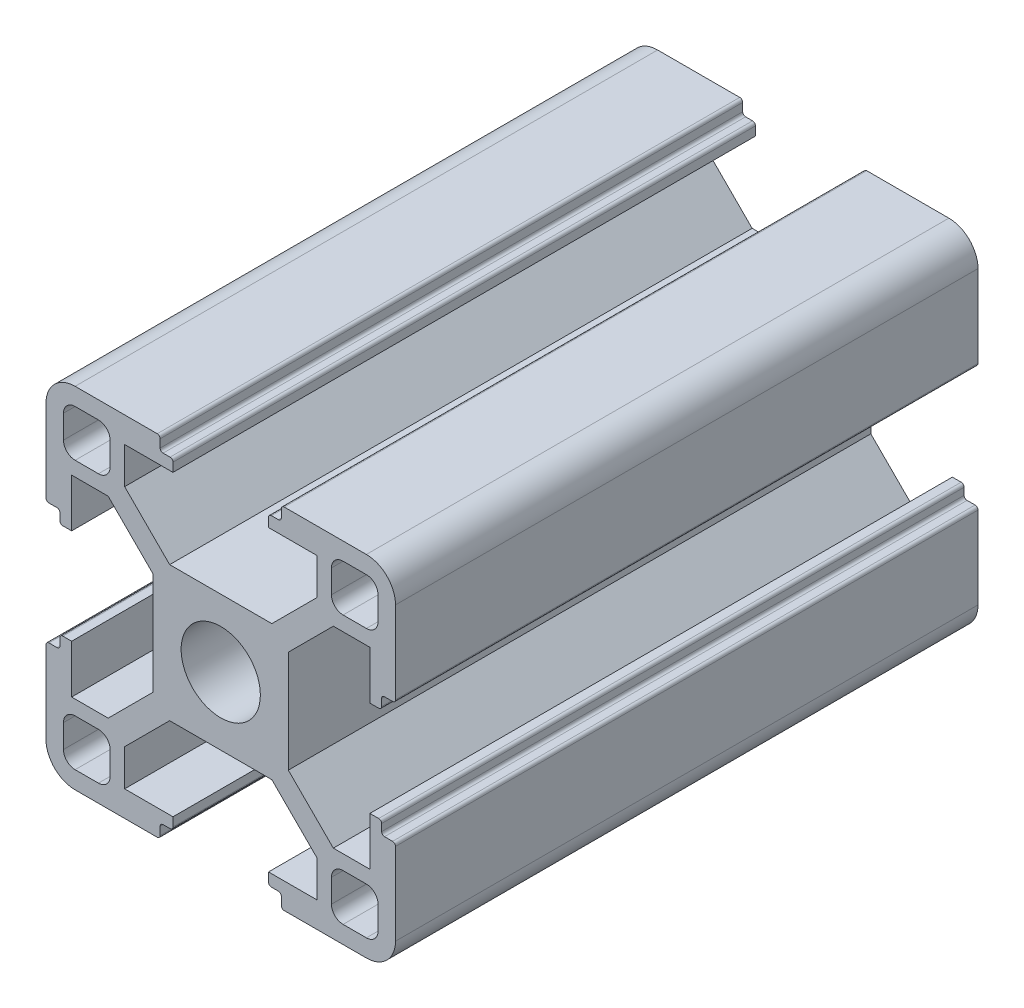
SolidWorks part; units mm, degrees
ref_plane "Front Plane" through (0, 0, 0) normal (0, 0, 1) x (1, 0, 0)
ref_plane "Top Plane" through (0, 0, 0) normal (0, 1, 0) x (1, 0, 0)
ref_plane "Right Plane" through (0, 0, 0) normal (1, 0, 0) x (0, 0, -1)
sketch "Sketch1" plane through (0, 0, 0) normal (0, 0, 1) x (1, 0, 0)
  line L0 (0, -5.8) -> (0, 5.8) construction
  line L1 (0, 0) -> (-15, 15) construction
  line L2 (-15, 15) -> (-5.2, 15)
  line L3 (-5.2, 15) -> (-5.2, 13.8083)
  line L4 (-5.2, 13.8083) -> (-4.1, 13.8083)
  line L5 (-4.1, 13.8083) -> (-4.1, 12.8)
  line L6 (-4.1, 12.8) -> (-8.25, 12.8)
  line L7 (-8.25, 12.8) -> (-8.25, 9.6642)
  line L8 (-8.25, 9.6642) -> (-4.3858, 5.8)
  line L9 (-4.3858, 5.8) -> (4.3858, 5.8)
  line L10 (-5.8, 4.3858) -> (-5.8, -4.3858)
  line L11 (-9.6642, 8.25) -> (-5.8, 4.3858)
  line L12 (-12.8, 8.25) -> (-9.6642, 8.25)
  line L13 (-12.8, 4.1) -> (-12.8, 8.25)
  line L14 (-13.8083, 4.1) -> (-12.8, 4.1)
  line L15 (-13.8083, 5.2) -> (-13.8083, 4.1)
  line L16 (-15, 5.2) -> (-13.8083, 5.2)
  line L17 (-15, 15) -> (-15, 5.2)
  line L18 (0, 0) -> (15, 15) construction
  line L19 (15, 15) -> (15, 5.2)
  line L20 (15, 5.2) -> (13.8083, 5.2)
  line L21 (13.8083, 5.2) -> (13.8083, 4.1)
  line L22 (13.8083, 4.1) -> (12.8, 4.1)
  line L23 (12.8, 4.1) -> (12.8, 8.25)
  line L24 (12.8, 8.25) -> (9.6642, 8.25)
  line L25 (9.6642, 8.25) -> (5.8, 4.3858)
  line L26 (5.8, 4.3858) -> (5.8, -4.3858)
  line L27 (8.25, 9.6642) -> (4.3858, 5.8)
  line L28 (8.25, 12.8) -> (8.25, 9.6642)
  line L29 (4.1, 12.8) -> (8.25, 12.8)
  line L30 (4.1, 13.8083) -> (4.1, 12.8)
  line L31 (5.2, 13.8083) -> (4.1, 13.8083)
  line L32 (5.2, 15) -> (5.2, 13.8083)
  line L33 (15, 15) -> (5.2, 15)
  line L34 (0, 0) -> (3.5826, 0) construction
  line L35 (0, 0) -> (15, -15) construction
  line L36 (0, 0) -> (-15, -15) construction
  line L37 (15, -15) -> (5.2, -15)
  line L38 (5.2, -15) -> (5.2, -13.8083)
  line L39 (5.2, -13.8083) -> (4.1, -13.8083)
  line L40 (4.1, -13.8083) -> (4.1, -12.8)
  line L41 (4.1, -12.8) -> (8.25, -12.8)
  line L42 (8.25, -12.8) -> (8.25, -9.6642)
  line L43 (8.25, -9.6642) -> (4.3858, -5.8)
  line L44 (9.6642, -8.25) -> (5.8, -4.3858)
  line L45 (12.8, -8.25) -> (9.6642, -8.25)
  line L46 (12.8, -4.1) -> (12.8, -8.25)
  line L47 (13.8083, -4.1) -> (12.8, -4.1)
  line L48 (13.8083, -5.2) -> (13.8083, -4.1)
  line L49 (15, -5.2) -> (13.8083, -5.2)
  line L50 (15, -15) -> (15, -5.2)
  line L51 (-15, -15) -> (-15, -5.2)
  line L52 (-15, -5.2) -> (-13.8083, -5.2)
  line L53 (-13.8083, -5.2) -> (-13.8083, -4.1)
  line L54 (-13.8083, -4.1) -> (-12.8, -4.1)
  line L55 (-12.8, -4.1) -> (-12.8, -8.25)
  line L56 (-12.8, -8.25) -> (-9.6642, -8.25)
  line L57 (-9.6642, -8.25) -> (-5.8, -4.3858)
  line L58 (-4.3858, -5.8) -> (4.3858, -5.8)
  line L59 (-8.25, -9.6642) -> (-4.3858, -5.8)
  line L60 (-8.25, -12.8) -> (-8.25, -9.6642)
  line L61 (-4.1, -12.8) -> (-8.25, -12.8)
  line L62 (-4.1, -13.8083) -> (-4.1, -12.8)
  line L63 (-5.2, -13.8083) -> (-4.1, -13.8083)
  line L64 (-5.2, -15) -> (-5.2, -13.8083)
  line L65 (-15, -15) -> (-5.2, -15)
  point P30 (0, 5.8)
  point P48 (5.8, 0)
  point P61 (-5.8, 0)
  dimension "D2" = 15
  dimension "D3" = 1
  dimension "D4" = 4.1
  dimension "D5" = 5.2
  dimension "D6" = 2.2
  dimension "D7" = 8.25
  dimension "D8" = 9.2
extrude "Boss-Extrude1" add sketch "Sketch1" along normal blind 250
sketch "Sketch2" plane through (0, 0, 250) normal (0, 0, 1) x (1, 0, 0)
  line L0 (0, 0) -> (0, 17.0054) construction
  line L1 (0, 0) -> (20.7717, 0) construction
  line L2 (-5.2, 15) -> (-15, 15) construction
  line L3 (-12.5, 13.5) -> (-10.5, 13.5)
  line L4 (-13.5, 12.5) -> (-13.5, 10.5)
  line L5 (-12.5, 9.5) -> (-10.5, 9.5)
  line L6 (-9.5, 12.5) -> (-9.5, 10.5)
  line L7 (-13.5, 13.5) -> (-9.5, 9.5) construction
  line L8 (-13.5, 9.5) -> (-9.5, 13.5) construction
  line L9 (-15, 15) -> (-15, 5.2) construction
  line L10 (13.5, 9.5) -> (9.5, 13.5) construction
  line L11 (13.5, 13.5) -> (9.5, 9.5) construction
  line L12 (9.5, 12.5) -> (9.5, 10.5)
  line L13 (12.5, 9.5) -> (10.5, 9.5)
  line L14 (13.5, 12.5) -> (13.5, 10.5)
  line L15 (12.5, 13.5) -> (10.5, 13.5)
  line L16 (13.5, -13.5) -> (9.5, -9.5) construction
  line L17 (13.5, -9.5) -> (9.5, -13.5) construction
  line L18 (-13.5, -9.5) -> (-9.5, -13.5) construction
  line L19 (-13.5, -13.5) -> (-9.5, -9.5) construction
  line L20 (12.5, -13.5) -> (10.5, -13.5)
  line L21 (13.5, -12.5) -> (13.5, -10.5)
  line L22 (12.5, -9.5) -> (10.5, -9.5)
  line L23 (9.5, -12.5) -> (9.5, -10.5)
  line L24 (-9.5, -12.5) -> (-9.5, -10.5)
  line L25 (-12.5, -9.5) -> (-10.5, -9.5)
  line L26 (-13.5, -12.5) -> (-13.5, -10.5)
  line L27 (-12.5, -13.5) -> (-10.5, -13.5)
  arc A0 (-12.5, 13.5) -> (-13.5, 12.5) centre (-12.5, 12.5) ccw
  arc A1 (-13.5, 10.5) -> (-12.5, 9.5) centre (-12.5, 10.5) ccw
  arc A2 (-10.5, 9.5) -> (-9.5, 10.5) centre (-10.5, 10.5) ccw
  arc A3 (-10.5, 13.5) -> (-9.5, 12.5) centre (-10.5, 12.5) cw
  arc A4 (10.5, 13.5) -> (9.5, 12.5) centre (10.5, 12.5) ccw
  arc A5 (10.5, 9.5) -> (9.5, 10.5) centre (10.5, 10.5) cw
  arc A6 (13.5, 10.5) -> (12.5, 9.5) centre (12.5, 10.5) cw
  arc A7 (12.5, 13.5) -> (13.5, 12.5) centre (12.5, 12.5) cw
  arc A8 (12.5, -13.5) -> (13.5, -12.5) centre (12.5, -12.5) ccw
  arc A9 (13.5, -10.5) -> (12.5, -9.5) centre (12.5, -10.5) ccw
  arc A10 (10.5, -9.5) -> (9.5, -10.5) centre (10.5, -10.5) ccw
  arc A11 (10.5, -13.5) -> (9.5, -12.5) centre (10.5, -12.5) cw
  arc A12 (-10.5, -13.5) -> (-9.5, -12.5) centre (-10.5, -12.5) ccw
  arc A13 (-10.5, -9.5) -> (-9.5, -10.5) centre (-10.5, -10.5) cw
  arc A14 (-13.5, -10.5) -> (-12.5, -9.5) centre (-12.5, -10.5) cw
  arc A15 (-12.5, -13.5) -> (-13.5, -12.5) centre (-12.5, -12.5) cw
  circle A16 centre (0, 0) radius 3.4
  point P3 (-11.5, 11.5)
  point P41 (11.5, 11.5)
  point P74 (11.5, -11.5)
  point P75 (-11.5, -11.5)
  dimension "D5" = 1
  dimension "D6" = 6.8
  dimension "D1" = 1.5
  dimension "D2" = 1.5
  dimension "D3" = 4
  dimension "D4" = 4
extrude "Cut-Extrude1" cut sketch "Sketch2" against normal through all
fillet "Fillet1" radius 2.5 4 edges at (-15, -15, 125) (15, -15, 125) (15, 15, 125) (-15, 15, 125)
fillet "Fillet2" radius 0.25 24 edges at (-13.8083, 5.2, 125) (-13.8083, 4.1, 125) (-15, 5.2, 125) (-13.8083, -4.1, 125) (-13.8083, -5.2, 125) (-15, -5.2, 125) (-5.2, -15, 125) (-5.2, -13.8083, 125) (-4.1, -13.8083, 125) (4.1, -13.8083, 125) (5.2, -13.8083, 125) (5.2, -15, 125) (13.8083, -5.2, 125) (13.8083, -4.1, 125) (15, -5.2, 125) (13.8083, 4.1, 125) (13.8083, 5.2, 125) (15, 5.2, 125) (-4.1, 13.8083, 125) (-5.2, 13.8083, 125) (4.1, 13.8083, 125) (5.2, 13.8083, 125) (5.2, 15, 125) (-5.2, 15, 125)
sketch "Sketch3" plane through (0, 0, 0) normal (0, 0, -1) x (-1, 0, 0)
  line L0 (-12.5, 13.5) -> (-10.5, 13.5) construction
  line L1 (-10.5, 9.5) -> (-12.5, 9.5) construction
  line L2 (-9.5, 12.5) -> (-9.5, 10.5) construction
  line L3 (-13.5, 10.5) -> (-13.5, 12.5) construction
  line L4 (-9.5, 12.5) -> (-9.5, 10.5)
  line L5 (-12.5, 13.5) -> (-10.5, 13.5)
  line L6 (-13.5, 10.5) -> (-13.5, 12.5)
  line L7 (-10.5, 9.5) -> (-12.5, 9.5)
  line L8 (10.5, 13.5) -> (12.5, 13.5) construction
  line L9 (9.5, 10.5) -> (9.5, 12.5) construction
  line L10 (13.5, 12.5) -> (13.5, 10.5) construction
  line L11 (12.5, 9.5) -> (10.5, 9.5) construction
  line L12 (12.5, 9.5) -> (10.5, 9.5)
  line L13 (13.5, 12.5) -> (13.5, 10.5)
  line L14 (9.5, 10.5) -> (9.5, 12.5)
  line L15 (10.5, 13.5) -> (12.5, 13.5)
  line L16 (9.5, -12.5) -> (9.5, -10.5) construction
  line L17 (12.5, -13.5) -> (10.5, -13.5) construction
  line L18 (13.5, -10.5) -> (13.5, -12.5) construction
  line L19 (10.5, -9.5) -> (12.5, -9.5) construction
  line L20 (9.5, -12.5) -> (9.5, -10.5)
  line L21 (12.5, -13.5) -> (10.5, -13.5)
  line L22 (13.5, -10.5) -> (13.5, -12.5)
  line L23 (10.5, -9.5) -> (12.5, -9.5)
  line L24 (-9.5, -10.5) -> (-9.5, -12.5) construction
  line L25 (-10.5, -13.5) -> (-12.5, -13.5) construction
  line L26 (-13.5, -12.5) -> (-13.5, -10.5) construction
  line L27 (-12.5, -9.5) -> (-10.5, -9.5) construction
  line L28 (-9.5, -10.5) -> (-9.5, -12.5)
  line L29 (-10.5, -13.5) -> (-12.5, -13.5)
  line L30 (-13.5, -12.5) -> (-13.5, -10.5)
  line L31 (-12.5, -9.5) -> (-10.5, -9.5)
  line L60 (12.8, 4.1) -> (13.5583, 4.1)
  line L61 (13.8083, 4.35) -> (13.8083, 4.95)
  line L62 (14.0583, 5.2) -> (14.75, 5.2)
  line L63 (15, 5.45) -> (15, 12.5)
  line L64 (12.5, 15) -> (5.45, 15)
  line L65 (5.2, 14.75) -> (5.2, 14.0583)
  line L66 (4.95, 13.8083) -> (4.35, 13.8083)
  line L67 (4.1, 13.5583) -> (4.1, 12.8)
  line L68 (4.1, 12.8) -> (8.25, 12.8)
  line L69 (8.25, 12.8) -> (8.25, 9.6642)
  line L70 (8.25, 9.6642) -> (4.3858, 5.8)
  line L71 (4.3858, 5.8) -> (-4.3858, 5.8)
  line L72 (-4.3858, 5.8) -> (-8.25, 9.6642)
  line L73 (-8.25, 9.6642) -> (-8.25, 12.8)
  line L74 (-8.25, 12.8) -> (-4.1, 12.8)
  line L75 (-4.1, 12.8) -> (-4.1, 13.5583)
  line L76 (-4.35, 13.8083) -> (-4.95, 13.8083)
  line L77 (-5.2, 14.0583) -> (-5.2, 14.75)
  line L78 (-5.45, 15) -> (-12.5, 15)
  line L79 (-15, 12.5) -> (-15, 5.45)
  line L80 (-14.75, 5.2) -> (-14.0583, 5.2)
  line L81 (-13.8083, 4.95) -> (-13.8083, 4.35)
  line L82 (-13.5583, 4.1) -> (-12.8, 4.1)
  line L83 (-12.8, 4.1) -> (-12.8, 8.25)
  line L84 (-12.8, 8.25) -> (-9.6642, 8.25)
  line L85 (-9.6642, 8.25) -> (-5.8, 4.3858)
  line L86 (-5.8, 4.3858) -> (-5.8, -4.3858)
  line L87 (-5.8, -4.3858) -> (-9.6642, -8.25)
  line L88 (-9.6642, -8.25) -> (-12.8, -8.25)
  line L89 (-12.8, -8.25) -> (-12.8, -4.1)
  line L90 (-12.8, -4.1) -> (-13.5583, -4.1)
  line L91 (-13.8083, -4.35) -> (-13.8083, -4.95)
  line L92 (-14.0583, -5.2) -> (-14.75, -5.2)
  line L93 (-15, -5.45) -> (-15, -12.5)
  line L94 (-12.5, -15) -> (-5.45, -15)
  line L95 (-5.2, -14.75) -> (-5.2, -14.0583)
  line L96 (-4.95, -13.8083) -> (-4.35, -13.8083)
  line L97 (-4.1, -13.5583) -> (-4.1, -12.8)
  line L98 (-4.1, -12.8) -> (-8.25, -12.8)
  line L99 (-8.25, -12.8) -> (-8.25, -9.6642)
  line L100 (-8.25, -9.6642) -> (-4.3858, -5.8)
  line L101 (-4.3858, -5.8) -> (4.3858, -5.8)
  line L102 (4.3858, -5.8) -> (8.25, -9.6642)
  line L103 (8.25, -9.6642) -> (8.25, -12.8)
  line L104 (8.25, -12.8) -> (4.1, -12.8)
  line L105 (4.1, -12.8) -> (4.1, -13.5583)
  line L106 (4.35, -13.8083) -> (4.95, -13.8083)
  line L107 (5.2, -14.0583) -> (5.2, -14.75)
  line L108 (5.45, -15) -> (12.5, -15)
  line L109 (15, -12.5) -> (15, -5.45)
  line L110 (14.75, -5.2) -> (14.0583, -5.2)
  line L111 (13.8083, -4.95) -> (13.8083, -4.35)
  line L112 (13.5583, -4.1) -> (12.8, -4.1)
  line L113 (12.8, -4.1) -> (12.8, -8.25)
  line L114 (12.8, -8.25) -> (9.6642, -8.25)
  line L115 (9.6642, -8.25) -> (5.8, -4.3858)
  line L116 (5.8, -4.3858) -> (5.8, 4.3858)
  line L117 (5.8, 4.3858) -> (9.6642, 8.25)
  line L118 (9.6642, 8.25) -> (12.8, 8.25)
  line L119 (12.8, 8.25) -> (12.8, 4.1)
  line L120 (12.8, 4.1) -> (13.5583, 4.1)
  line L121 (13.8083, 4.35) -> (13.8083, 4.95)
  line L122 (14.0583, 5.2) -> (14.75, 5.2)
  line L123 (15, 5.45) -> (15, 12.5)
  line L124 (12.5, 15) -> (5.45, 15)
  line L125 (5.2, 14.75) -> (5.2, 14.0583)
  line L126 (4.95, 13.8083) -> (4.35, 13.8083)
  line L127 (4.1, 13.5583) -> (4.1, 12.8)
  line L128 (4.1, 12.8) -> (8.25, 12.8)
  line L129 (8.25, 12.8) -> (8.25, 9.6642)
  line L130 (8.25, 9.6642) -> (4.3858, 5.8)
  line L131 (4.3858, 5.8) -> (-4.3858, 5.8)
  line L132 (-4.3858, 5.8) -> (-8.25, 9.6642)
  line L133 (-8.25, 9.6642) -> (-8.25, 12.8)
  line L134 (-8.25, 12.8) -> (-4.1, 12.8)
  line L135 (-4.1, 12.8) -> (-4.1, 13.5583)
  line L136 (-4.35, 13.8083) -> (-4.95, 13.8083)
  line L137 (-5.2, 14.0583) -> (-5.2, 14.75)
  line L138 (-5.45, 15) -> (-12.5, 15)
  line L139 (-15, 12.5) -> (-15, 5.45)
  line L140 (-14.75, 5.2) -> (-14.0583, 5.2)
  line L141 (-13.8083, 4.95) -> (-13.8083, 4.35)
  line L142 (-13.5583, 4.1) -> (-12.8, 4.1)
  line L143 (-12.8, 4.1) -> (-12.8, 8.25)
  line L144 (-12.8, 8.25) -> (-9.6642, 8.25)
  line L145 (-9.6642, 8.25) -> (-5.8, 4.3858)
  line L146 (-5.8, 4.3858) -> (-5.8, -4.3858)
  line L147 (-5.8, -4.3858) -> (-9.6642, -8.25)
  line L148 (-9.6642, -8.25) -> (-12.8, -8.25)
  line L149 (-12.8, -8.25) -> (-12.8, -4.1)
  line L150 (-12.8, -4.1) -> (-13.5583, -4.1)
  line L151 (-13.8083, -4.35) -> (-13.8083, -4.95)
  line L152 (-14.0583, -5.2) -> (-14.75, -5.2)
  line L153 (-15, -5.45) -> (-15, -12.5)
  line L154 (-12.5, -15) -> (-5.45, -15)
  line L155 (-5.2, -14.75) -> (-5.2, -14.0583)
  line L156 (-4.95, -13.8083) -> (-4.35, -13.8083)
  line L157 (-4.1, -13.5583) -> (-4.1, -12.8)
  line L158 (-4.1, -12.8) -> (-8.25, -12.8)
  line L159 (-8.25, -12.8) -> (-8.25, -9.6642)
  line L160 (-8.25, -9.6642) -> (-4.3858, -5.8)
  line L161 (-4.3858, -5.8) -> (4.3858, -5.8)
  line L162 (4.3858, -5.8) -> (8.25, -9.6642)
  line L163 (8.25, -9.6642) -> (8.25, -12.8)
  line L164 (8.25, -12.8) -> (4.1, -12.8)
  line L165 (4.1, -12.8) -> (4.1, -13.5583)
  line L166 (4.35, -13.8083) -> (4.95, -13.8083)
  line L167 (5.2, -14.0583) -> (5.2, -14.75)
  line L168 (5.45, -15) -> (12.5, -15)
  line L169 (15, -12.5) -> (15, -5.45)
  line L170 (14.75, -5.2) -> (14.0583, -5.2)
  line L171 (13.8083, -4.95) -> (13.8083, -4.35)
  line L172 (13.5583, -4.1) -> (12.8, -4.1)
  line L173 (12.8, -4.1) -> (12.8, -8.25)
  line L174 (12.8, -8.25) -> (9.6642, -8.25)
  line L175 (9.6642, -8.25) -> (5.8, -4.3858)
  line L176 (5.8, -4.3858) -> (5.8, 4.3858)
  line L177 (5.8, 4.3858) -> (9.6642, 8.25)
  line L178 (9.6642, 8.25) -> (12.8, 8.25)
  line L179 (12.8, 8.25) -> (12.8, 4.1)
  circle A0 centre (0, 0) radius 3.4 construction
  circle A1 centre (0, 0) radius 3.4
  arc A2 (-12.5, 13.5) -> (-13.5, 12.5) centre (-12.5, 12.5) ccw construction
  arc A3 (-9.5, 12.5) -> (-10.5, 13.5) centre (-10.5, 12.5) ccw construction
  arc A4 (-13.5, 10.5) -> (-12.5, 9.5) centre (-12.5, 10.5) ccw construction
  arc A5 (-10.5, 9.5) -> (-9.5, 10.5) centre (-10.5, 10.5) ccw construction
  arc A6 (-9.5, 12.5) -> (-10.5, 13.5) centre (-10.5, 12.5) ccw
  arc A7 (-12.5, 13.5) -> (-13.5, 12.5) centre (-12.5, 12.5) ccw
  arc A8 (-13.5, 10.5) -> (-12.5, 9.5) centre (-12.5, 10.5) ccw
  arc A9 (-10.5, 9.5) -> (-9.5, 10.5) centre (-10.5, 10.5) ccw
  arc A10 (13.5, 12.5) -> (12.5, 13.5) centre (12.5, 12.5) ccw construction
  arc A11 (10.5, 13.5) -> (9.5, 12.5) centre (10.5, 12.5) ccw construction
  arc A12 (12.5, 9.5) -> (13.5, 10.5) centre (12.5, 10.5) ccw construction
  arc A13 (9.5, 10.5) -> (10.5, 9.5) centre (10.5, 10.5) ccw construction
  arc A14 (9.5, 10.5) -> (10.5, 9.5) centre (10.5, 10.5) ccw
  arc A15 (12.5, 9.5) -> (13.5, 10.5) centre (12.5, 10.5) ccw
  arc A16 (10.5, 13.5) -> (9.5, 12.5) centre (10.5, 12.5) ccw
  arc A17 (13.5, 12.5) -> (12.5, 13.5) centre (12.5, 12.5) ccw
  arc A18 (10.5, -9.5) -> (9.5, -10.5) centre (10.5, -10.5) ccw construction
  arc A19 (9.5, -12.5) -> (10.5, -13.5) centre (10.5, -12.5) ccw construction
  arc A20 (12.5, -13.5) -> (13.5, -12.5) centre (12.5, -12.5) ccw construction
  arc A21 (13.5, -10.5) -> (12.5, -9.5) centre (12.5, -10.5) ccw construction
  arc A22 (10.5, -9.5) -> (9.5, -10.5) centre (10.5, -10.5) ccw
  arc A23 (9.5, -12.5) -> (10.5, -13.5) centre (10.5, -12.5) ccw
  arc A24 (12.5, -13.5) -> (13.5, -12.5) centre (12.5, -12.5) ccw
  arc A25 (13.5, -10.5) -> (12.5, -9.5) centre (12.5, -10.5) ccw
  arc A26 (-9.5, -10.5) -> (-10.5, -9.5) centre (-10.5, -10.5) ccw construction
  arc A27 (-10.5, -13.5) -> (-9.5, -12.5) centre (-10.5, -12.5) ccw construction
  arc A28 (13.5583, 4.1) -> (13.8083, 4.35) centre (13.5583, 4.35) ccw
  arc A29 (14.0583, 5.2) -> (13.8083, 4.95) centre (14.0583, 4.95) ccw
  arc A30 (14.75, 5.2) -> (15, 5.45) centre (14.75, 5.45) ccw
  arc A31 (15, 12.5) -> (12.5, 15) centre (12.5, 12.5) ccw
  arc A32 (5.45, 15) -> (5.2, 14.75) centre (5.45, 14.75) ccw
  arc A33 (4.95, 13.8083) -> (5.2, 14.0583) centre (4.95, 14.0583) ccw
  arc A34 (4.35, 13.8083) -> (4.1, 13.5583) centre (4.35, 13.5583) ccw
  arc A35 (-4.1, 13.5583) -> (-4.35, 13.8083) centre (-4.35, 13.5583) ccw
  arc A36 (-5.2, 14.0583) -> (-4.95, 13.8083) centre (-4.95, 14.0583) ccw
  arc A37 (-5.2, 14.75) -> (-5.45, 15) centre (-5.45, 14.75) ccw
  arc A38 (-12.5, 15) -> (-15, 12.5) centre (-12.5, 12.5) ccw
  arc A39 (-15, 5.45) -> (-14.75, 5.2) centre (-14.75, 5.45) ccw
  arc A40 (-13.8083, 4.95) -> (-14.0583, 5.2) centre (-14.0583, 4.95) ccw
  arc A41 (-13.8083, 4.35) -> (-13.5583, 4.1) centre (-13.5583, 4.35) ccw
  arc A42 (-13.5583, -4.1) -> (-13.8083, -4.35) centre (-13.5583, -4.35) ccw
  arc A43 (-14.0583, -5.2) -> (-13.8083, -4.95) centre (-14.0583, -4.95) ccw
  arc A44 (-14.75, -5.2) -> (-15, -5.45) centre (-14.75, -5.45) ccw
  arc A45 (-15, -12.5) -> (-12.5, -15) centre (-12.5, -12.5) ccw
  arc A46 (-5.45, -15) -> (-5.2, -14.75) centre (-5.45, -14.75) ccw
  arc A47 (-4.95, -13.8083) -> (-5.2, -14.0583) centre (-4.95, -14.0583) ccw
  arc A48 (-4.35, -13.8083) -> (-4.1, -13.5583) centre (-4.35, -13.5583) ccw
  arc A49 (4.1, -13.5583) -> (4.35, -13.8083) centre (4.35, -13.5583) ccw
  arc A50 (5.2, -14.0583) -> (4.95, -13.8083) centre (4.95, -14.0583) ccw
  arc A51 (5.2, -14.75) -> (5.45, -15) centre (5.45, -14.75) ccw
  arc A52 (12.5, -15) -> (15, -12.5) centre (12.5, -12.5) ccw
  arc A53 (15, -5.45) -> (14.75, -5.2) centre (14.75, -5.45) ccw
  arc A54 (13.8083, -4.95) -> (14.0583, -5.2) centre (14.0583, -4.95) ccw
  arc A55 (13.8083, -4.35) -> (13.5583, -4.1) centre (13.5583, -4.35) ccw
  arc A56 (13.5583, 4.1) -> (13.8083, 4.35) centre (13.5583, 4.35) ccw
  arc A57 (14.0583, 5.2) -> (13.8083, 4.95) centre (14.0583, 4.95) ccw
  arc A58 (14.75, 5.2) -> (15, 5.45) centre (14.75, 5.45) ccw
  arc A59 (15, 12.5) -> (12.5, 15) centre (12.5, 12.5) ccw
  arc A60 (5.45, 15) -> (5.2, 14.75) centre (5.45, 14.75) ccw
  arc A61 (4.95, 13.8083) -> (5.2, 14.0583) centre (4.95, 14.0583) ccw
  arc A62 (4.35, 13.8083) -> (4.1, 13.5583) centre (4.35, 13.5583) ccw
  arc A63 (-4.1, 13.5583) -> (-4.35, 13.8083) centre (-4.35, 13.5583) ccw
  arc A64 (-5.2, 14.0583) -> (-4.95, 13.8083) centre (-4.95, 14.0583) ccw
  arc A65 (-5.2, 14.75) -> (-5.45, 15) centre (-5.45, 14.75) ccw
  arc A66 (-12.5, 15) -> (-15, 12.5) centre (-12.5, 12.5) ccw
  arc A67 (-15, 5.45) -> (-14.75, 5.2) centre (-14.75, 5.45) ccw
  arc A68 (-13.8083, 4.95) -> (-14.0583, 5.2) centre (-14.0583, 4.95) ccw
  arc A69 (-13.8083, 4.35) -> (-13.5583, 4.1) centre (-13.5583, 4.35) ccw
  arc A70 (-13.5583, -4.1) -> (-13.8083, -4.35) centre (-13.5583, -4.35) ccw
  arc A71 (-14.0583, -5.2) -> (-13.8083, -4.95) centre (-14.0583, -4.95) ccw
  arc A72 (-14.75, -5.2) -> (-15, -5.45) centre (-14.75, -5.45) ccw
  arc A73 (-15, -12.5) -> (-12.5, -15) centre (-12.5, -12.5) ccw
  arc A74 (-5.45, -15) -> (-5.2, -14.75) centre (-5.45, -14.75) ccw
  arc A75 (-4.95, -13.8083) -> (-5.2, -14.0583) centre (-4.95, -14.0583) ccw
  arc A76 (-4.35, -13.8083) -> (-4.1, -13.5583) centre (-4.35, -13.5583) ccw
  arc A77 (4.1, -13.5583) -> (4.35, -13.8083) centre (4.35, -13.5583) ccw
  arc A78 (5.2, -14.0583) -> (4.95, -13.8083) centre (4.95, -14.0583) ccw
  arc A79 (5.2, -14.75) -> (5.45, -15) centre (5.45, -14.75) ccw
  arc A80 (12.5, -15) -> (15, -12.5) centre (12.5, -12.5) ccw
  arc A81 (15, -5.45) -> (14.75, -5.2) centre (14.75, -5.45) ccw
  arc A82 (13.8083, -4.95) -> (14.0583, -5.2) centre (14.0583, -4.95) ccw
  arc A83 (13.8083, -4.35) -> (13.5583, -4.1) centre (13.5583, -4.35) ccw
  arc A84 (-13.5, -12.5) -> (-12.5, -13.5) centre (-12.5, -12.5) ccw construction
  arc A85 (-12.5, -9.5) -> (-13.5, -10.5) centre (-12.5, -10.5) ccw construction
  arc A86 (-9.5, -10.5) -> (-10.5, -9.5) centre (-10.5, -10.5) ccw
  arc A87 (-10.5, -13.5) -> (-9.5, -12.5) centre (-10.5, -12.5) ccw
  arc A88 (-13.5, -12.5) -> (-12.5, -13.5) centre (-12.5, -12.5) ccw
  arc A89 (-12.5, -9.5) -> (-13.5, -10.5) centre (-12.5, -10.5) ccw
  dimension "D1" = 0
extrude "Cut-Extrude3" cut sketch "Sketch3" against normal blind 200
